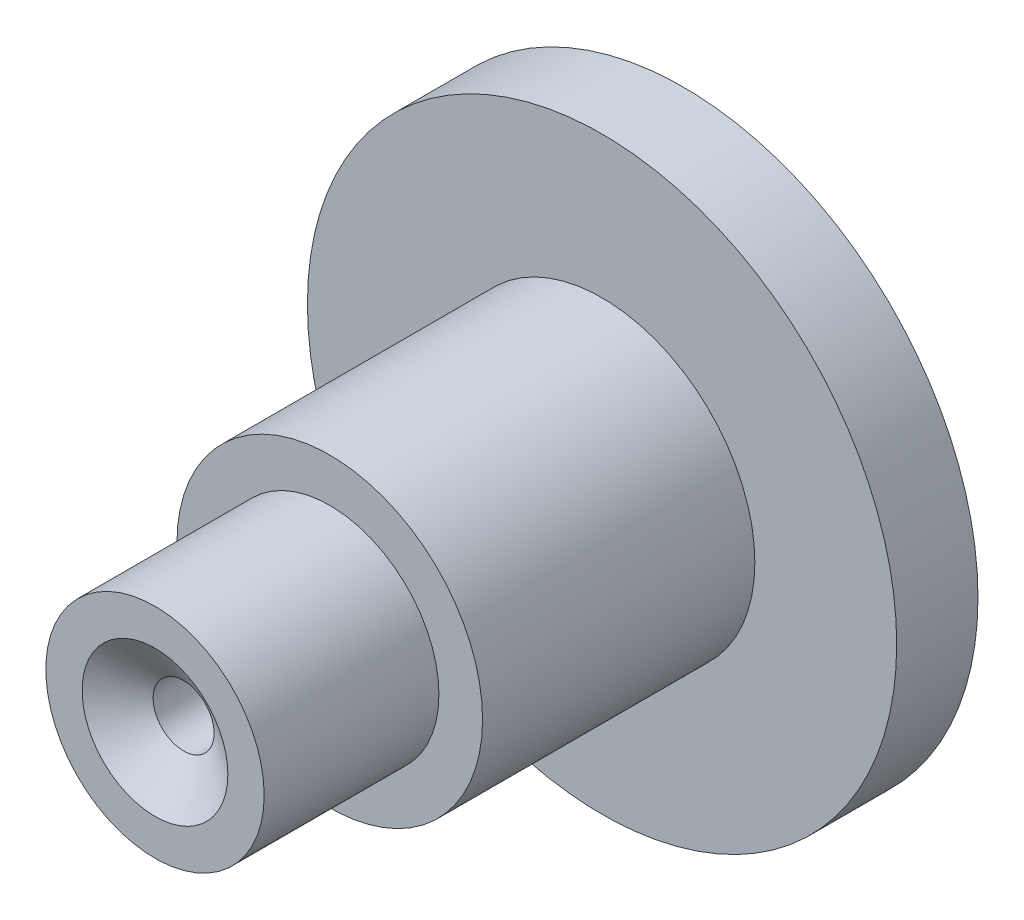
SolidWorks part; units mm, degrees
ref_plane "Front Plane" through (0, 0, 0) normal (0, 0, 1) x (1, 0, 0)
ref_plane "Top Plane" through (0, 0, 0) normal (0, 1, 0) x (1, 0, 0)
ref_plane "Right Plane" through (0, 0, 0) normal (1, 0, 0) x (0, 0, -1)
sketch "Sketch1" plane through (0, 0, 0) normal (1, 0, 0) x (0, 0, -1)
  line L0 (0, 0) -> (0, 46.0375)
  line L1 (0, 46.0375) -> (-12.7, 46.0375)
  line L2 (-12.7, 46.0375) -> (-12.7, 23.876)
  line L3 (-12.7, 23.876) -> (-55.245, 23.876)
  line L4 (-55.245, 23.876) -> (-55.245, 17.0595)
  line L5 (-55.245, 17.0595) -> (-82.55, 17.0595)
  line L7 (-78.0777, 4.7625) -> (-57.15, 4.7625)
  line L8 (-57.15, 4.7625) -> (-57.15, 0)
  line L9 (-57.15, 0) -> (0, 0)
  line L10 (-82.55, 17.0595) -> (-82.55, 11.3858)
  line L11 (-82.55, 11.3858) -> (-78.0777, 4.7625)
  point P3 (-2.4383, 11.5099)
  point P13 (-11.2311, 8.1747)
  point P14 (-8.536, 3.155)
  point P15 (-3.8533, 0)
  point P16 (-40.9732, 34.6032)
  point P17 (-30.5451, 41.8854)
  point P18 (0, 0)
  point P19 (-30.9529, 7.6298)
  point P20 (-40.0579, 22.2581)
  point P21 (-20.0247, 33.6338)
  point P22 (-9.6557, 32.0231)
  point P23 (-18.8166, 6.8557)
  point P24 (-32.105, 7.2584)
  point P25 (-14.2865, 0)
  point P26 (-37.6418, 24.9762)
  point P27 (-49.0175, 7.2584)
  point P28 (-75.3928, 11.3858)
  point P29 (-57.2724, 9.525)
  point P30 (-61.7926, 9.525)
  point P31 (-78.0777, 9.525)
  dimension "D1" = 46.0375
  dimension "D2" = 69.85
  dimension "D3" = 23.876
  dimension "D4" = 12.7
  dimension "D5" = 4.7625
  dimension "D6" = 42.545
  dimension "D7" = 25.4
revolve "Revolve1" add sketch "Sketch1" angle 360 about L9
